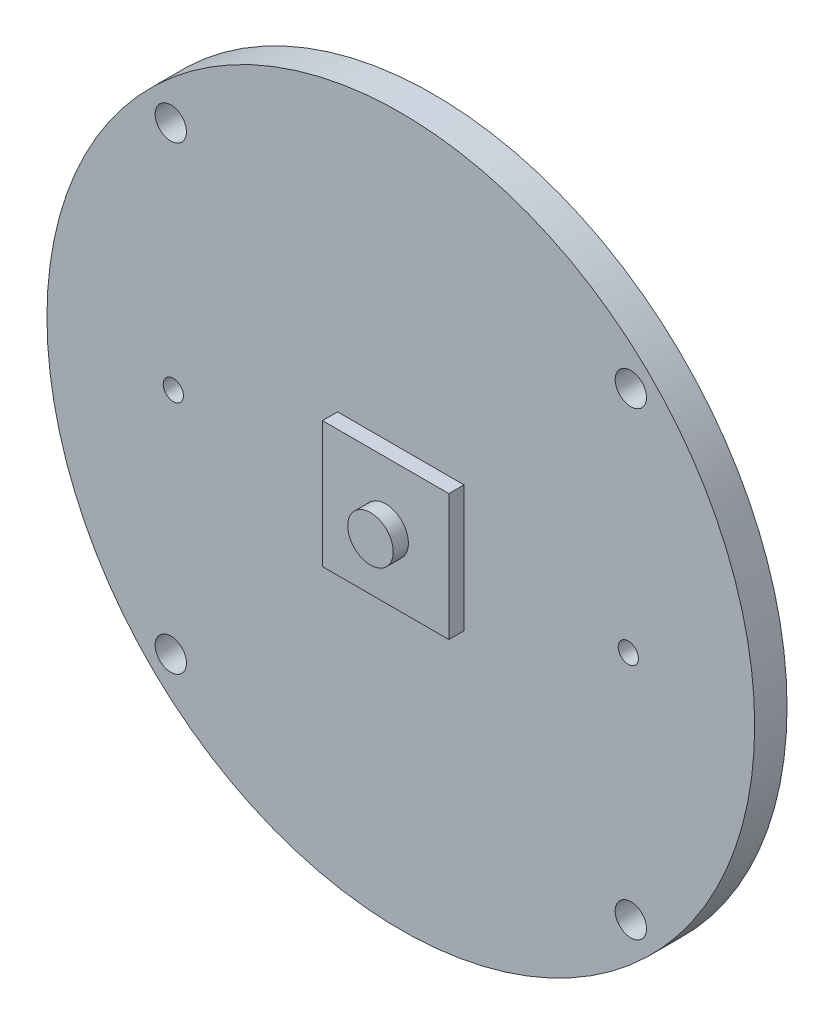
SolidWorks part; units mm, degrees
ref_plane "Front Plane" through (0, 0, 0) normal (0, 0, 1) x (1, 0, 0)
ref_plane "Top Plane" through (0, 0, 0) normal (0, 1, 0) x (1, 0, 0)
ref_plane "Right Plane" through (0, 0, 0) normal (1, 0, 0) x (0, 0, -1)
sketch "Sketch1" plane through (0, 0, 0) normal (0, 0, 1) x (1, 0, 0)
  circle A0 centre (0, 0) radius 17.78
  dimension "D1" = 35.56
extrude "Boss-Extrude1" add sketch "Sketch1" along normal blind 1.6256
sketch "Sketch2" plane through (0, 0, 1.6256) normal (0, 0, 1) x (1, 0, 0)
  line L0 (11.43, 0) -> (-11.43, 0) construction
  line L1 (0, 0) -> (0, -17.78) construction
  circle A0 centre (0, 0) radius 17.78 construction
  circle A1 centre (-11.43, 0) radius 0.508
  circle A2 centre (11.43, 0) radius 0.508
extrude "Cut-Extrude1" cut sketch "Sketch2" against normal through all
sketch "Sketch3" plane through (0, 0, 1.6256) normal (0, 0, 1) x (1, 0, 0)
  line L1 (-3.175, 3.175) -> (3.175, 3.175)
  line L2 (-3.175, 3.175) -> (-3.175, -3.175)
  line L3 (-3.175, -3.175) -> (3.175, -3.175)
  line L4 (3.175, 3.175) -> (3.175, -3.175)
  line L5 (-3.175, 3.175) -> (3.175, -3.175) construction
  line L6 (-3.175, -3.175) -> (3.175, 3.175) construction
  point P0 (0, 0)
extrude "Boss-Extrude2" add sketch "Sketch3" along normal blind 0.762
sketch "Sketch4" plane through (0, 0, 2.3876) normal (0, 0, 1) x (1, 0, 0)
  circle A0 centre (0, 0) radius 1.143
extrude "Boss-Extrude3" add sketch "Sketch4" along normal blind 0.762
sketch "Sketch5" plane through (0, 0, 1.6256) normal (0, 0, 1) x (1, 0, 0)
  line L1 (-11.557, 11.557) -> (11.557, 11.557) construction
  line L2 (-11.557, 11.557) -> (-11.557, -11.557) construction
  line L3 (-11.557, -11.557) -> (11.557, -11.557) construction
  line L4 (11.557, 11.557) -> (11.557, -11.557) construction
  line L5 (-11.557, 11.557) -> (11.557, -11.557) construction
  line L6 (-11.557, -11.557) -> (11.557, 11.557) construction
  circle A0 centre (0, 0) radius 16.3441 construction
  circle A1 centre (0, 0) radius 17.78 construction
  circle A2 centre (-11.557, 11.557) radius 0.7874
  circle A3 centre (11.557, 11.557) radius 0.7874
  circle A4 centre (11.557, -11.557) radius 0.7874
  circle A5 centre (-11.557, -11.557) radius 0.7874
  point P3 (16.3441, 0)
  point P4 (17.78, 0)
  dimension "D1" = 1.5748
  dimension "D2" = 23.114
extrude "Cut-Extrude2" cut sketch "Sketch5" against normal through all
